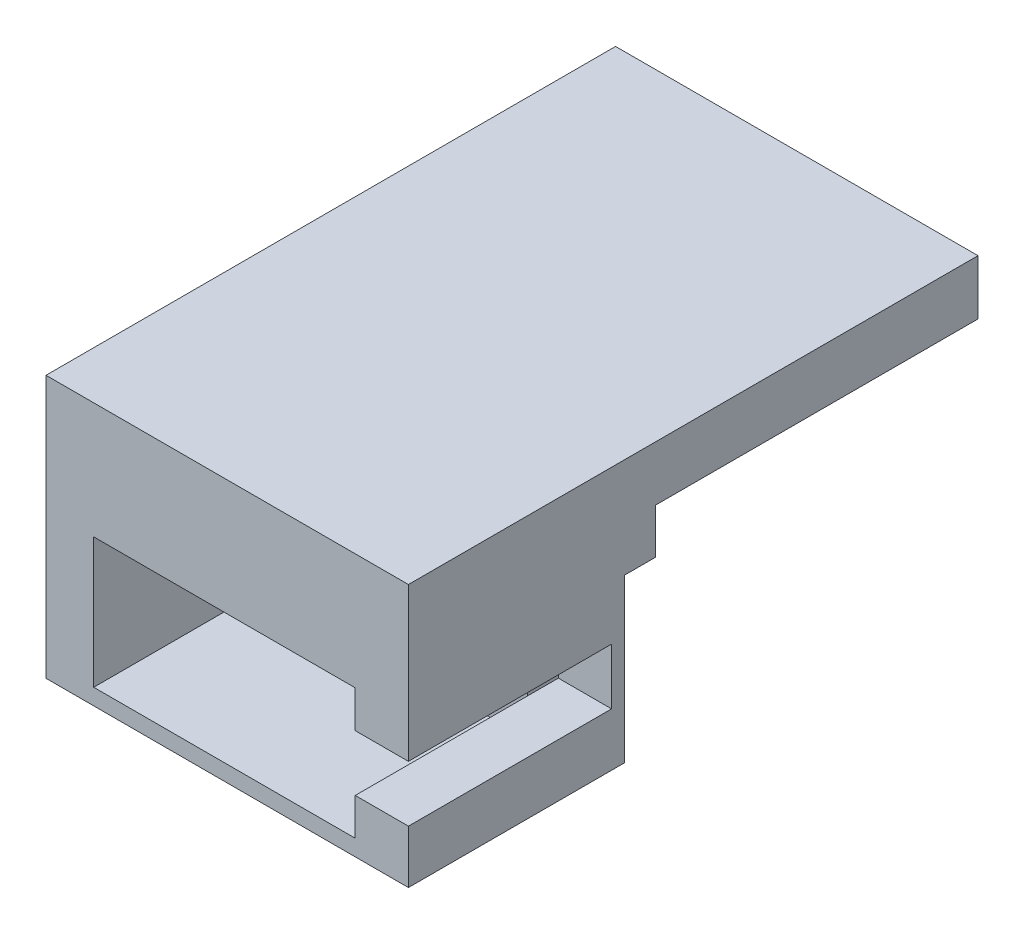
SolidWorks part; units mm, degrees
ref_plane "Front Plane" through (0, 0, 0) normal (0, 0, 1) x (1, 0, 0)
ref_plane "Top Plane" through (0, 0, 0) normal (0, 1, 0) x (1, 0, 0)
ref_plane "Right Plane" through (0, 0, 0) normal (1, 0, 0) x (0, 0, -1)
sketch "Sketch1" plane through (0, 0, 0) normal (0, 0, 1) x (1, 0, 0)
  line L0 (-3.3841, 0) -> (3.9364, 0) construction
  line L1 (-3.3841, -1.3864) -> (-3.3841, 23.8136)
  line L2 (-3.3841, 23.8136) -> (52.8159, 23.8136)
  line L3 (-3.3841, -1.3864) -> (52.8159, -1.3864)
  line L4 (52.8159, -1.3864) -> (52.8159, 6.8636)
  line L5 (52.8159, 23.8136) -> (52.8159, 15.5636)
  line L6 (52.8159, 15.5636) -> (44.5659, 15.5636)
  line L7 (44.5659, 15.5636) -> (44.5659, 6.8636)
  line L8 (44.5659, 6.8636) -> (52.8159, 6.8636)
  dimension "D1" = 56.2
  dimension "D2" = 25.2
  dimension "D3" = 8.25
  dimension "D4" = 8.25
  dimension "D5" = 8.25
  dimension "D6" = 56.2
extrude "Boss-Extrude1" add sketch "Sketch1" along normal blind 31.5
sketch "Sketch2" plane through (0, 0, 31.5) normal (0, 0, 1) x (1, 0, 0)
  line L0 (-3.3841, 11.2136) -> (44.5659, 11.2136) construction
  line L1 (-3.3841, 23.8136) -> (-3.3841, -1.3864) construction
  line L2 (44.5659, 6.8636) -> (44.5659, 15.5636) construction
  line L3 (4.0159, 21.3136) -> (44.5659, 21.3136)
  line L4 (44.5659, 21.3136) -> (44.5659, 15.5636)
  line L5 (44.5659, 15.5636) -> (44.5659, 6.8636)
  line L6 (44.5659, 6.8636) -> (44.5659, 1.1136)
  line L7 (44.5659, 1.1136) -> (4.0159, 1.1136)
  line L8 (4.0159, 1.1136) -> (4.0159, 21.3136)
  line L9 (52.8159, 23.8136) -> (-3.3841, 23.8136) construction
  line L10 (-3.3841, -1.3864) -> (52.8159, -1.3864) construction
  dimension "D1" = 2.5
  dimension "D2" = 7.4
  dimension "D3" = 2.5
  dimension "D4" = 20.2
extrude "Cut-Extrude1" cut sketch "Sketch2" against normal blind 26.7
sketch "Sketch3" plane through (0, 0, 0) normal (0, 0, -1) x (-1, 0, 0)
  line L0 (-52.8159, 23.8136) -> (3.3841, 23.8136)
  line L1 (3.3841, 23.8136) -> (3.3841, -1.3864)
  line L2 (3.3841, -1.3864) -> (-52.8159, -1.3864)
  line L3 (-52.8159, -1.3864) -> (-52.8159, 23.8136)
extrude "Boss-Extrude2" add sketch "Sketch3" along normal blind 2 contours L3 L0 L1 L2
sketch "Sketch5" plane through (0, 23.8136, 0) normal (0, 1, 0) x (1, 0, 0)
  line L0 (-3.3841, -13.1789) -> (52.8159, -13.1789)
  line L1 (-3.3841, -31.5) -> (-3.3841, 2) construction
  line L2 (52.8159, -31.5) -> (52.8159, 2) construction
  line L3 (52.8159, -13.1789) -> (52.8159, 6.8211)
  line L4 (52.8159, 6.8211) -> (-3.3841, 6.8211)
  line L5 (-3.3841, 6.8211) -> (-3.3841, -13.1789)
  dimension "D1" = 20
extrude "Boss-Extrude4" add sketch "Sketch5" along normal blind 7
sketch "Sketch6" plane through (0, 30.8136, 0) normal (0, 1, 0) x (1, 0, 0)
  line L0 (-3.3841, -3.1789) -> (52.8159, -3.1789)
  line L1 (-3.3841, 6.8211) -> (-3.3841, -13.1789) construction
  line L2 (52.8159, -13.1789) -> (52.8159, 6.8211) construction
  line L3 (52.8159, -3.1789) -> (52.8159, 56.8211)
  line L4 (52.8159, 56.8211) -> (-3.3841, 56.8211)
  line L5 (-3.3841, 56.8211) -> (-3.3841, -3.1789)
  dimension "D1" = 60
extrude "Boss-Extrude5" add sketch "Sketch6" along normal blind 8.5 contours L5 L0 L3 L4
sketch "Sketch10" plane through (0, 30.8136, 0) normal (0, -1, 0) x (1, 0, 0)
  line L0 (28.9223, -40.9479) -> (45.7223, -40.9479)
  line L1 (28.9223, -48.5479) -> (45.7223, -48.5479)
  line L2 (29.9405, -44.7479) -> (49.5223, -44.7479) construction
  arc A0 (28.9223, -40.9479) -> (28.9223, -48.5479) centre (22.3405, -44.7479) ccw
  arc A1 (45.7223, -40.9479) -> (45.7223, -48.5479) centre (45.7223, -44.7479) cw
  dimension "D4" = 7.6
  dimension "D1" = 7.6
  dimension "D2" = 16.8
  dimension "D3" = 16.8
extrude "Cut-Extrude2" cut sketch "Sketch10" against normal blind 5.5
sketch "Sketch11" plane through (0, 36.3136, 0) normal (0, -1, 0) x (1, 0, 0)
  line L0 (16.2188, -44.7479) -> (37.3915, -44.7479) construction
  line L1 (22.3405, -52.3479) -> (22.3405, -37.1479) construction
  arc A1 (28.9223, -40.9479) -> (28.9223, -48.5479) centre (22.3405, -44.7479) ccw construction
  circle A2 centre (22.3405, -44.7479) radius 2.3257
extrude "Cut-Extrude3" cut sketch "Sketch11" against normal blind 0.5
sketch "Sketch12" plane through (0, 0, 13.1789) normal (0, 0, 1) x (1, 0, 0)
  line L0 (-3.3841, 30.8136) -> (52.8159, 30.8136)
  line L1 (52.8159, 30.8136) -> (52.8159, 23.8136)
  line L2 (52.8159, 23.8136) -> (-3.3841, 23.8136)
  line L3 (-3.3841, 23.8136) -> (-3.3841, 30.8136)
extrude "Boss-Extrude8" add sketch "Sketch12" along direction (0, 0, 1) on the side of the normal up to surface (18.3211 mm away)
sketch "Sketch18" plane through (0, 0, 3.1789) normal (0, 0, 1) x (1, 0, 0)
  line L0 (-3.3841, 39.3136) -> (52.8159, 39.3136)
  line L1 (52.8159, 39.3136) -> (52.8159, 30.8136)
  line L2 (52.8159, 30.8136) -> (-3.3841, 30.8136)
  line L3 (-3.3841, 30.8136) -> (-3.3841, 39.3136)
extrude "Boss-Extrude9" add sketch "Sketch18" along direction (0, 0, 1) on the side of the normal up to surface (28.3211 mm away) contours L3 L0 L1 L2
fillet "Fillet5" radius 5 2 edges at (28.9223, 33.5636, -40.9479) (28.9223, 33.5636, -48.5479)
